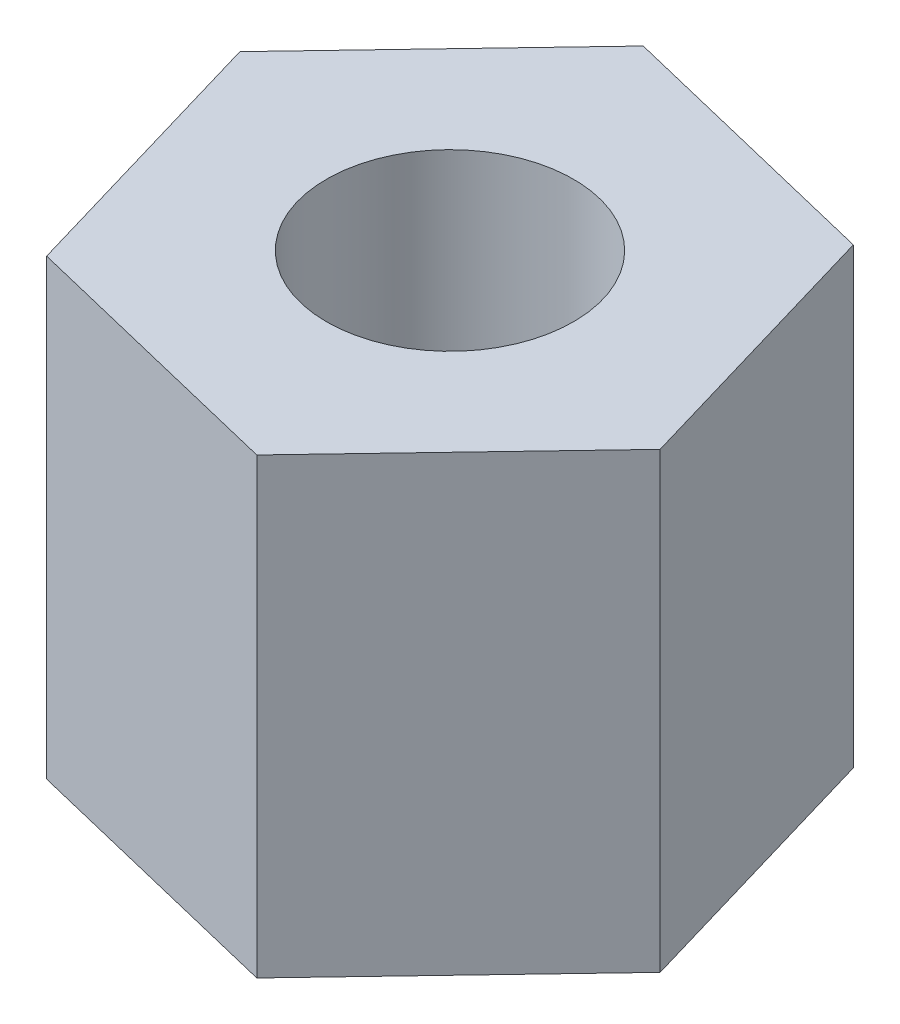
SolidWorks part; units mm, degrees
material "Thornel VCB-20 Carbon Cloth"
ref_plane "Front Plane" through (0, 0, 0) normal (0, 0, 1) x (1, 0, 0)
ref_plane "Top Plane" through (0, 0, 0) normal (0, 1, 0) x (1, 0, 0)
ref_plane "Right Plane" through (0, 0, 0) normal (1, 0, 0) x (0, 0, -1)
sketch "Sketch1" plane through (0, 0, 0) normal (0, 1, 0) x (1, 0, 0)
  line L1 (0.9773, -3.3234) -> (3.3668, -0.8153)
  line L2 (3.3668, -0.8153) -> (2.3895, 2.508)
  line L3 (2.3895, 2.508) -> (-0.9773, 3.3234)
  line L4 (-0.9773, 3.3234) -> (-3.3668, 0.8153)
  line L5 (-3.3668, 0.8153) -> (-2.3895, -2.508)
  line L6 (-2.3895, -2.508) -> (0.9773, -3.3234)
  circle A0 centre (0, 0) radius 1.5
  circle A1 centre (0, 0) radius 3 construction
  dimension "D1" = 3
  dimension "D2" = 6
extrude "Boss-Extrude1" add sketch "Sketch1" along normal mid plane 5.5
